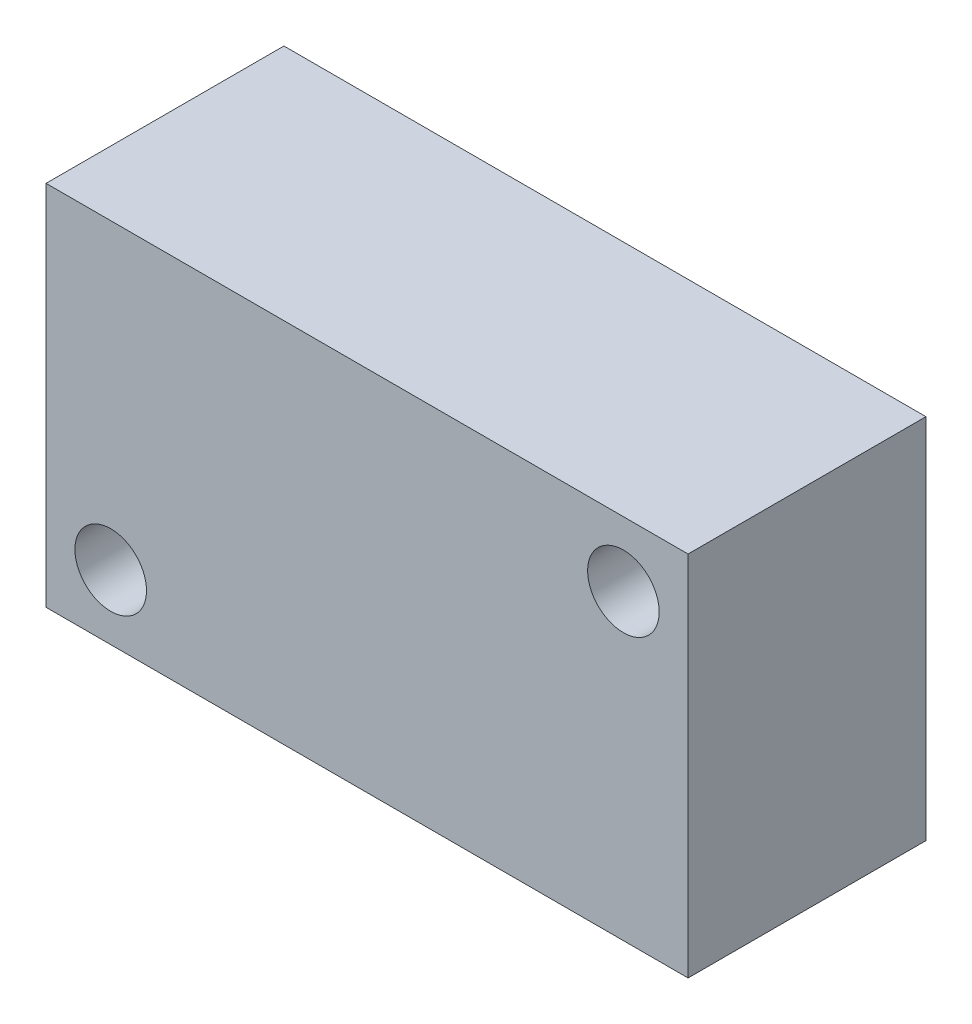
SolidWorks part; units mm, degrees
ref_plane "正面" through (0, 0, 0) normal (0, 0, 1) x (1, 0, 0)
ref_plane "平面" through (0, 0, 0) normal (0, 1, 0) x (1, 0, 0)
ref_plane "右側面" through (0, 0, 0) normal (1, 0, 0) x (0, 0, -1)
sketch "ｽｹｯﾁ2" plane through (0, 0, 0) normal (0, 0, 1) x (1, 0, 0)
  line L0 (13.9, 15.9) -> (13.9, 0) construction
  line L1 (0, 0) -> (27.8, 0)
  line L2 (0, 0) -> (0, 15.9)
  line L3 (0, 15.9) -> (27.8, 15.9)
  line L4 (27.8, 0) -> (27.8, 15.9)
  line L6 (25, 13.1) -> (2.8, 13.1) construction
  line L7 (25, 13.1) -> (25, 2.8) construction
  line L8 (25, 2.8) -> (2.8, 2.8) construction
  line L9 (2.8, 13.1) -> (2.8, 2.8) construction
  line L10 (25, 13.1) -> (2.8, 2.8) construction
  line L11 (25, 2.8) -> (2.8, 13.1) construction
  circle A0 centre (2.8, 2.8) radius 1.55
  circle A1 centre (25, 13.1) radius 1.55
  point P11 (13.9, 7.95)
  point P12 (20.5081, 10.4715)
  dimension "D1" = 10.3
  dimension "D2" = 3.1
  dimension "D4" = 15.9
  dimension "D3" = 27.8
  dimension "D5" = 22.2
extrude "ﾎﾞｽ - 押し出し1" add sketch "ｽｹｯﾁ2" along normal blind 10.3
sketch "ｽｹｯﾁ3" plane through (0, 0, 10.3) normal (0, 0, 1) x (1, 0, 0)
  line L0 (25, 13.1) -> (16.9, 13.1)
  line L1 (16.9, 13.1) -> (16.9, 15.9)
  dimension "D1" = 8.1
  dimension "D2" = 2.8
